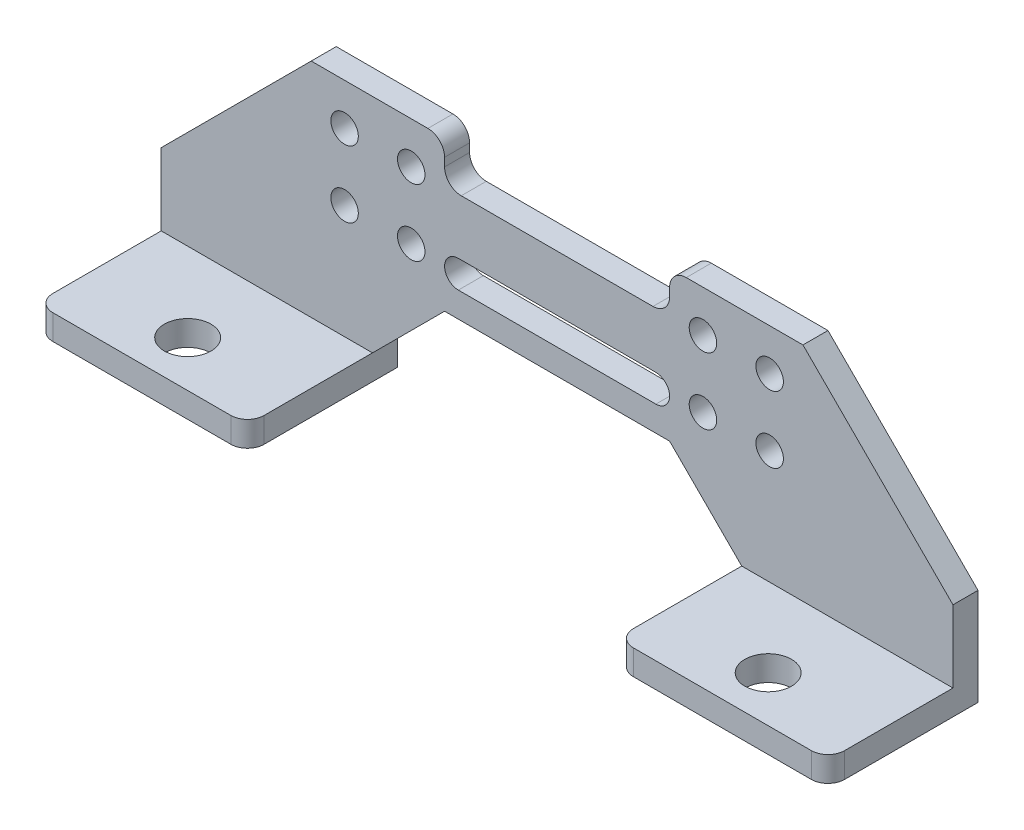
SolidWorks part; units mm, degrees
ref_plane "前视基准面" through (0, 0, 0) normal (0, 0, 1) x (1, 0, 0)
ref_plane "上视基准面" through (0, 0, 0) normal (0, 1, 0) x (1, 0, 0)
ref_plane "右视基准面" through (0, 0, 0) normal (1, 0, 0) x (0, 0, -1)
sketch "草图1" plane through (0, 0, 0) normal (0, 0, 1) x (1, 0, 0)
  line L0 (0, 0) -> (0, 8)
  line L1 (12, -0.325) -> (39, -0.325)
  line L2 (43, 8) -> (39, 8)
  line L3 (51, 0) -> (51, 8)
  line L4 (8, 0) -> (8, 8)
  line L5 (43, 0) -> (43, 8)
  line L6 (8, 8) -> (12, 8)
  line L7 (12, -5) -> (3.35, -13.65)
  line L8 (-4, 8) -> (-4, 13)
  line L9 (-4, 13) -> (55, 13)
  line L10 (12, -13.65) -> (39, -13.65)
  line L11 (55, 13) -> (55, 8)
  line L12 (39, -13.65) -> (39, 13)
  line L13 (-4, 13) -> (55, 13)
  line L14 (-4, 13) -> (-4, -13.65)
  line L15 (55, 13) -> (55, -13.65)
  line L16 (-4, -13.65) -> (55, -13.65)
  line L17 (12, 8) -> (39, 8)
  line L18 (12, -5) -> (39, -5)
  line L19 (13.65, 1.325) -> (37.35, 1.325)
  line L20 (-4, 13) -> (-11.928, 5.072)
  line L21 (37.35, -1.975) -> (13.65, -1.975)
  line L22 (55, 13) -> (64.6983, 3.3017)
  line L23 (39, -5) -> (47.65, -13.65)
  line L24 (-4, 13) -> (-4, 0)
  line L25 (11.9694, 0) -> (11.9694, -5)
  line L26 (-4, 13) -> (-17, 0)
  line L27 (55, 13) -> (68, 0)
  line L28 (68, 0) -> (73, -5)
  line L29 (73, -5) -> (73, -13.65)
  line L30 (73, -13.65) -> (55, -13.65)
  line L31 (-17, 0) -> (-22, -5)
  line L32 (-22, -5) -> (-22, -13.65)
  line L33 (-22, -13.65) -> (-4, -13.65)
  line L34 (12, 8) -> (12, 13)
  circle A0 centre (0, 8) radius 1.65
  circle A1 centre (8, 8) radius 1.65
  circle A2 centre (43, 8) radius 1.65
  circle A3 centre (51, 8) radius 1.65
  circle A4 centre (43, 0) radius 1.65
  circle A5 centre (51, 0) radius 1.65
  circle A6 centre (8, 0) radius 1.65
  circle A7 centre (0, 0) radius 1.65
  circle A9 centre (13.65, -0.325) radius 1.65
  circle A11 centre (37.35, -0.325) radius 1.65
extrude "凸台-拉伸1" add sketch "草图1" along normal blind 3
sketch "草图4" plane through (0, 0, 0) normal (0, 0, 1) x (1, 0, 0)
  line L0 (-22, -13.65) -> (3.35, -13.65)
  line L1 (-22, -13.65) -> (-22, -16.65)
  line L2 (3.35, -13.65) -> (3.35, -16.65)
  line L3 (-22, -16.65) -> (3.35, -16.65)
  line L4 (47.65, -13.65) -> (73, -13.65)
  line L5 (47.65, -13.65) -> (47.65, -16.65)
  line L6 (73, -13.65) -> (73, -16.65)
  line L7 (47.65, -16.65) -> (73, -16.65)
extrude "凸台-拉伸3" add sketch "草图4" along normal blind 18
sketch "草图5" plane through (0, -16.65, 0) normal (0, -1, 0) x (1, 0, 0)
  line L0 (-22, 3) -> (3.35, 3)
  line L1 (-22, 3) -> (-22, 18)
  line L2 (3.35, 3) -> (3.35, 18)
  line L3 (-22, 18) -> (3.35, 18)
  line L4 (47.65, 18) -> (73, 18)
  line L5 (47.65, 18) -> (47.65, 3)
  line L6 (73, 18) -> (73, 3)
  line L7 (47.65, 3) -> (73, 3)
  line L9 (60.325, 10.5) -> (60.325, 12.5)
  circle A0 centre (60.325, 12.5) radius 2.8
  circle A1 centre (-9.325, 12.5) radius 2.8
extrude "切除-拉伸2" cut sketch "草图5" against normal blind 18
fillet "圆角2" radius 2 8 edges at (39, 13, 1.5) (12, 13, 1.5) (12, 8, 1.5) (39, 8, 1.5) (-22, -15.15, 18) (3.35, -15.15, 18) (47.65, -15.15, 18) (73, -15.15, 18)
